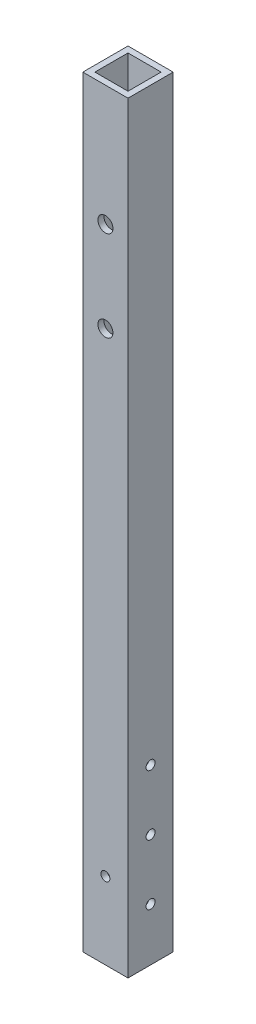
SolidWorks part; units mm, degrees
material "6061 合金"
ref_plane "前视基准面" through (0, 0, 0) normal (0, 0, 1) x (1, 0, 0)
ref_plane "上视基准面" through (0, 0, 0) normal (0, 1, 0) x (1, 0, 0)
ref_plane "右视基准面" through (0, 0, 0) normal (1, 0, 0) x (0, 0, -1)
sketch "草图1" plane through (0, 0, 0) normal (0, 1, 0) x (1, 0, 0)
  line L1 (-7.5, 7.5) -> (7.5, 7.5)
  line L2 (-7.5, 7.5) -> (-7.5, -7.5)
  line L3 (-7.5, -7.5) -> (7.5, -7.5)
  line L4 (7.5, 7.5) -> (7.5, -7.5)
  line L5 (-7.5, 7.5) -> (7.5, -7.5) construction
  line L6 (-7.5, -7.5) -> (7.5, 7.5) construction
  point P0 (0, 0)
  dimension "D1" = 15
  dimension "D2" = 15
extrude "凸台-拉伸1" add sketch "草图1" along normal blind 253
sketch "草图2" plane through (0, 253, 0) normal (0, 1, 0) x (1, 0, 0)
  line L1 (-5.5, 5.5) -> (5.5, 5.5)
  line L2 (-5.5, 5.5) -> (-5.5, -5.5)
  line L3 (-5.5, -5.5) -> (5.5, -5.5)
  line L4 (5.5, 5.5) -> (5.5, -5.5)
  line L5 (-5.5, 5.5) -> (5.5, -5.5) construction
  line L6 (-5.5, -5.5) -> (5.5, 5.5) construction
  point P0 (0, 0)
extrude "切除-拉伸1" cut sketch "草图2" against normal blind 253
sketch "草图3" plane through (7.5, 0, 0) normal (1, 0, 0) x (0, 0, -1)
  line L0 (7.5, 253) -> (7.5, 0) construction
  line L1 (-7.5, 0) -> (7.5, 0) construction
  circle A0 centre (0, 17.5) radius 1.5
  circle A1 centre (0, 37.5) radius 1.5
  circle A2 centre (0, 57.5) radius 1.5
  dimension "D1" = 7.5
  dimension "D2" = 7.5
  dimension "D3" = 7.5
  dimension "D4" = 17.5
  dimension "D5" = 20
  dimension "D6" = 20
extrude "切除-拉伸2" cut sketch "草图3" against normal blind 15
sketch "草图4" plane through (0, 0, -7.5) normal (0, 0, -1) x (-1, 0, 0)
  line L0 (-7.5, 0) -> (7.5, 0) construction
  circle A0 centre (0, 25.5) radius 1.5
  dimension "D1" = 25.5
extrude "切除-拉伸3" cut sketch "草图4" against normal blind 15
sketch "草图5" plane through (0, 0, -7.5) normal (0, 0, -1) x (-1, 0, 0)
  line L0 (-7.5, 253) -> (7.5, 253) construction
  circle A0 centre (0, 213) radius 2.5
  circle A1 centre (0, 183) radius 2.5
  dimension "D1" = 5
  dimension "D2" = 5
  dimension "D3" = 30
  dimension "D4" = 40
extrude "切除-拉伸4" cut sketch "草图5" against normal blind 15
